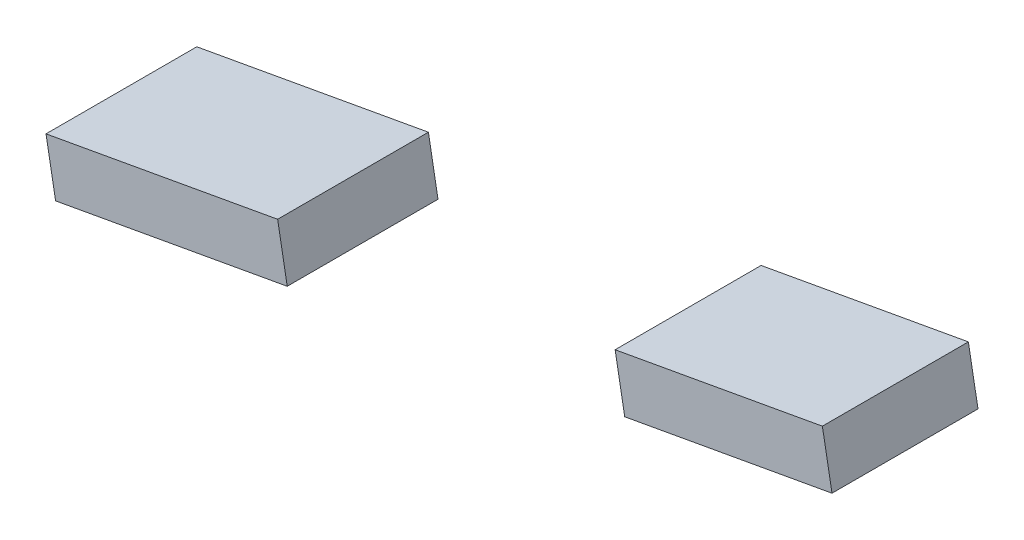
SolidWorks part; units mm, degrees
ref_plane "Front Plane" through (0, 0, 0) normal (0, 0, 1) x (1, 0, 0)
ref_plane "Top Plane" through (0, 0, 0) normal (0, 1, 0) x (1, 0, 0)
ref_plane "Right Plane" through (0, 0, 0) normal (1, 0, 0) x (0, 0, -1)
sketch "Sketch1" plane through (8, -44.2832, 0) normal (0.1778, -0.9841, 0) x (0.9841, 0.1778, 0)
  line L1 (-89.0818, 86.9798) -> (-36.903, 86.9798)
  line L2 (-89.0818, 86.9798) -> (-89.0818, 53.55)
  line L3 (-89.0818, 53.55) -> (-36.903, 53.55)
  line L4 (-36.903, 86.9798) -> (-36.903, 53.55)
  line L5 (40.5692, 88.3948) -> (87.2647, 88.3948)
  line L6 (40.5692, 88.3948) -> (40.5692, 56.0263)
  line L7 (40.5692, 56.0263) -> (87.2647, 56.0263)
  line L8 (87.2647, 88.3948) -> (87.2647, 56.0263)
extrude "Boss-Extrude1" add sketch "Sketch1" along normal blind 12 contours L2 L1 L4 L3 | L6 L5 L8 L7
